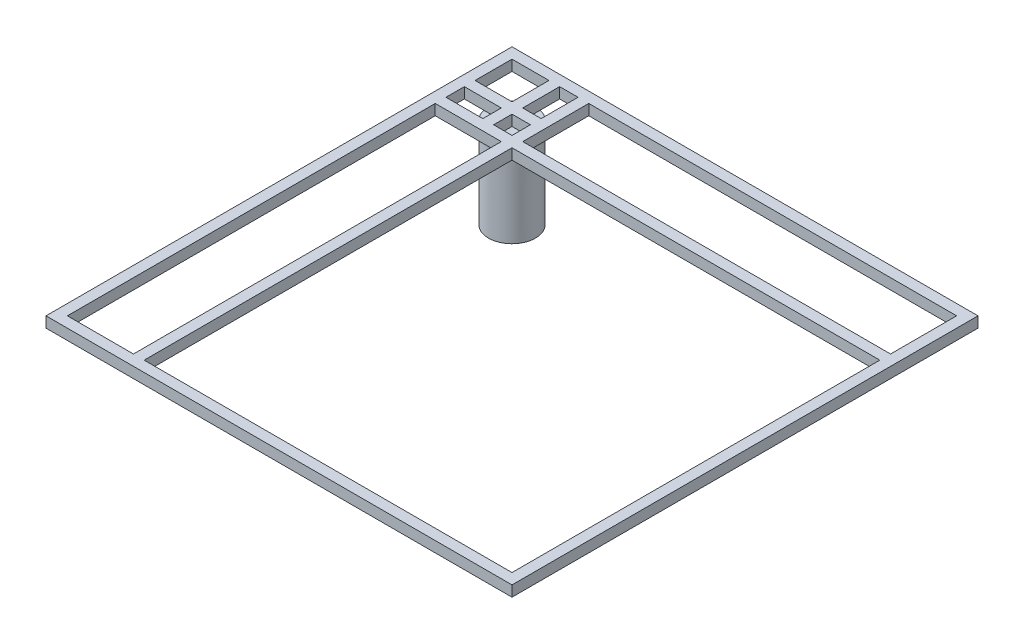
SolidWorks part; units mm, degrees
material "1023 Carbon Steel Sheet (SS)"
ref_plane "Front Plane" through (0, 0, 0) normal (0, 0, 1) x (1, 0, 0)
ref_plane "Top Plane" through (0, 0, 0) normal (0, 1, 0) x (1, 0, 0)
ref_plane "Right Plane" through (0, 0, 0) normal (1, 0, 0) x (0, 0, -1)
sketch "Sketch1" plane through (0, 0, 0) normal (0, 1, 0) x (1, 0, 0)
  line L0 (100, 554.516) -> (100, 425.7733) construction
  line L1 (0, 0) -> (567.538, 0)
  line L2 (0, 0) -> (0, 567.538)
  line L3 (0, 567.538) -> (567.538, 567.538)
  line L4 (567.538, 0) -> (567.538, 567.538)
  line L5 (13.022, 13.022) -> (93.489, 13.022)
  line L6 (13.022, 13.022) -> (13.022, 461.027)
  line L7 (13.022, 554.516) -> (58.022, 554.516)
  line L8 (554.516, 13.022) -> (554.516, 461.027)
  line L10 (93.489, 554.516) -> (93.489, 509.516)
  line L12 (106.511, 461.027) -> (106.511, 13.022)
  line L13 (13.022, 474.049) -> (58.022, 474.049)
  line L15 (13.022, 461.027) -> (93.489, 461.027)
  line L17 (13.022, 467.538) -> (159.2186, 467.538) construction
  line L18 (106.511, 554.516) -> (554.516, 554.516)
  line L19 (106.511, 474.049) -> (554.516, 474.049)
  line L20 (106.511, 461.027) -> (554.516, 461.027)
  line L21 (93.489, 461.027) -> (93.489, 13.022)
  line L22 (13.022, 474.049) -> (13.022, 496.494)
  line L23 (554.516, 474.049) -> (554.516, 554.516)
  line L24 (106.511, 13.022) -> (554.516, 13.022)
  line L25 (106.511, 554.516) -> (106.511, 474.049)
  line L26 (71.044, 474.049) -> (93.489, 474.049)
  line L28 (58.022, 474.049) -> (58.022, 496.494)
  line L30 (71.044, 474.049) -> (71.044, 496.494)
  line L31 (93.489, 496.494) -> (71.044, 496.494)
  line L33 (93.489, 509.516) -> (71.044, 509.516)
  line L35 (58.022, 496.494) -> (13.022, 496.494)
  line L36 (58.022, 509.516) -> (13.022, 509.516)
  line L37 (71.044, 509.516) -> (71.044, 554.516)
  line L38 (58.022, 509.516) -> (58.022, 554.516)
  line L39 (13.022, 509.516) -> (13.022, 554.516)
  line L40 (93.489, 496.494) -> (93.489, 474.049)
  line L41 (71.044, 554.516) -> (93.489, 554.516)
  dimension "D1" = 802.62
  dimension "D2" = 13.022
  dimension "D3" = 13.022
  dimension "D4" = 13.022
  dimension "D5" = 13.022
  dimension "D6" = 6.511
  dimension "D7" = 13.022
  dimension "D8" = 6.511
  dimension "D9" = 13.022
  dimension "D10" = 100
  dimension "D11" = 100
  dimension "D12" = 13.022
  dimension "D13" = 13.022
  dimension "D14" = 45
  dimension "D15" = 45
extrude "Boss-Extrude1" add sketch "Sketch1" along normal blind 13.022
sketch "Sketch2" plane through (0, 0, 0) normal (0, -1, 0) x (1, 0, 0)
  line L0 (58.022, -496.494) -> (71.044, -509.516) construction
  line L1 (71.044, -509.516) -> (71.044, -496.494) construction
  line L2 (71.044, -496.494) -> (58.022, -509.516) construction
  line L3 (58.022, -509.516) -> (58.022, -496.494) construction
  circle A2 centre (64.533, -503.005) radius 28.6
  dimension "D1" = 57.2
extrude "Boss-Extrude2" add sketch "Sketch2" along normal blind 110
